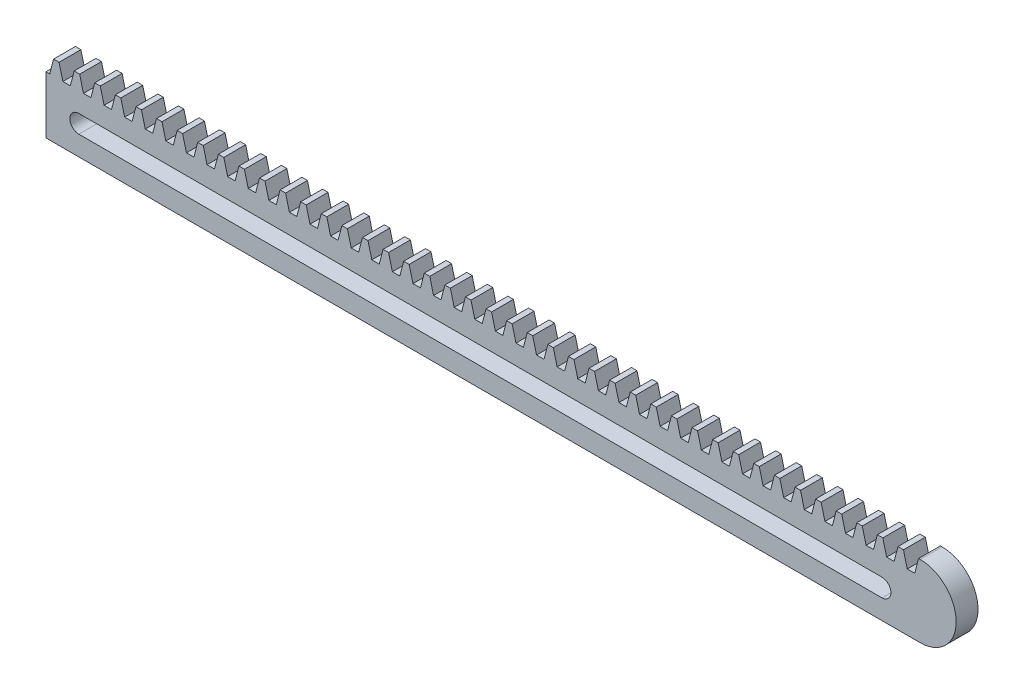
SolidWorks part; units mm, degrees
ref_plane "Plane1" through (0, 0, 0) normal (0, 0, 1) x (1, 0, 0)
ref_plane "Plane2" through (0, 0, 0) normal (0, 1, 0) x (1, 0, 0)
ref_plane "Plane3" through (0, 0, 0) normal (1, 0, 0) x (0, 0, -1)
sketch "HoldingSke" plane through (0, 0, 0) normal (0, 1, 0) x (1, 0, 0)
  line L0 (0, 0) -> (0.0464, 0.3301)
  line L1 (-15, 0) -> (100, 0) construction
  line L2 (0, 0) -> (-2.1039, 2.3779)
  line L3 (0, 0) -> (-11.863, 4.5341)
  line L4 (0, 0) -> (6.2122, 5.9991)
  line L5 (0, 0) -> (-23.7986, -8.8762)
  line L6 (0, 0) -> (-10.5278, -7.1032)
  line L9 (-67.7845, 28.3722) -> (319.4745, 128.5242)
  line L10 (-76.2, 5.3779) -> (-46.2, 5.3779)
  line L11 (0, 0) -> (-10, 0)
  line L12 (-76.2, 101.6) -> (-76.093, 101.6)
  line L13 (24.9733, 27.94) -> (52.9518, 28.4284)
  line L14 (24.9733, 27.94) -> (24.9743, 27.94)
  line L15 (24.9733, 27.94) -> (100.4006, 29.5858)
  circle A0 centre (0, 0) radius 19.05
  circle A1 centre (0, 0) radius 15
  circle A2 centre (0, 0) radius 12.7
  dimension "MPH" = 30
  dimension "Diameter" = 38.1
  dimension "Num_teeth" = 44
  dimension "Pitch" = 0.3333
  dimension "Width" = 10
  dimension "Show_teeth" = 998
  dimension "Thickness" = 12.7
  dimension "Ap" = 14.5
  dimension "Pitch_height" = 30
  dimension "Backlash" = 0.107
  dimension "Addendum_fac" = 1
  dimension "Dedendum_fac" = 1.25
  dimension "Clearance_fac" = 0.25
  dimension "Dedendum_add" = 0.001
  dimension "Length" = 400
  dimension "Module" = 3
sketch "BlankSke" plane through (0, 0, 0) normal (0, 0, 1) x (1, 0, 0)
  line L1 (0, 0) -> (400, 0)
  line L2 (0, 0) -> (0, 33)
  line L3 (0, 33) -> (400, 33)
  line L4 (400, 0) -> (400, 33)
  dimension "Length" = 400
  dimension "Blank_height" = 33
extrude "Blank" add sketch "BlankSke" against normal blind 10
sketch "TooCutSkeIll" plane through (0, 0, 0) normal (0, 0, 1) x (1, 0, 0)
  line L0 (-3.4298, 32.91) -> (-1.853, 26.813)
  line L1 (-1.1259, 26.25) -> (1.1259, 26.25)
  line L2 (1.853, 26.813) -> (3.4298, 32.91)
  line L3 (400, 33) -> (0, 33) construction
  line L4 (0, 0) -> (0, 64.897) construction
  line L5 (-13.208, 30) -> (12.954, 30) construction
  line L6 (0, 0) -> (400, 0) construction
  line L7 (2.6772, 30) -> (2.6772, 48.7463) construction
  line L8 (-2.6772, 30) -> (-2.6772, 48.7463) construction
  line L9 (3.546, 33) -> (3.546, 33.0254)
  line L10 (-3.546, 33) -> (-3.546, 33.0254)
  line L11 (-3.546, 33.0254) -> (3.546, 33.0254)
  arc A0 (1.1259, 26.25) -> (1.853, 26.813) centre (1.1259, 27.001) ccw
  arc A1 (-1.853, 26.813) -> (-1.1259, 26.25) centre (-1.1259, 27.001) ccw
  arc A2 (3.546, 33) -> (3.4298, 32.91) centre (3.546, 32.88) ccw
  arc A3 (-3.4298, 32.91) -> (-3.546, 33) centre (-3.546, 32.88) ccw
  dimension "Root_fillet" = 0.751
  dimension "Break_rad" = 0.12
  dimension "Pitch_height" = 30
  dimension "Gap_width" = 5.3544
  dimension "Dedendum" = 3.75
  dimension "Addendum_plus" = 3.0254
  dimension "Pressure_angle" = 14.5
extrude "ToothCutIll" [suppressed] cut sketch "TooCutSkeIll" against normal through all
sketch "TooCutSkeSim" plane through (0, 0, 0) normal (0, 0, 1) x (1, 0, 0)
  line L0 (1.7074, 26.25) -> (-1.7074, 26.25)
  line L1 (3.4596, 33.0254) -> (1.7074, 26.25)
  line L2 (0, 17.4625) -> (0, 53.467) construction
  line L3 (3.4596, 33.0254) -> (-3.4596, 33.0254)
  line L6 (-3.4596, 33.0254) -> (-1.7074, 26.25)
  line L9 (-2.6772, 30) -> (2.6772, 30) construction
  line L10 (0, 0) -> (400, 0) construction
  line L11 (2.6772, 30) -> (2.6772, 53.467) construction
  line L12 (-2.6772, 30) -> (-2.6772, 53.467) construction
  dimension "Pitch_height" = 30
  dimension "Pressure_angle" = 14.5
  dimension "Gap_width" = 5.3544
  dimension "Dedendum" = 3.75
  dimension "Addendum_plus" = 3.0254
extrude "ToothCutSim" cut sketch "TooCutSkeSim" against normal through all
pattern_linear "TeethCuts" count 43 spacing 9.4248 along (1, 0, 0) of "ToothCutIll", "ToothCutSim"
sketch "Sketch1" plane through (0, 0, 0) normal (0, 0, 1) x (1, 0, 0)
  line L0 (0, 26.25) -> (0, 0) construction
  line L1 (397.5481, 26.25) -> (397.5481, 0) construction
  line L2 (0, 0) -> (400, 0) construction
  line L3 (15, 13.125) -> (382.5481, 13.125) construction
  line L4 (15, 17.225) -> (382.5481, 17.225)
  line L5 (15, 9.025) -> (382.5481, 9.025)
  arc A0 (15, 17.225) -> (15, 9.025) centre (15, 13.125) ccw
  arc A1 (382.5481, 9.025) -> (382.5481, 17.225) centre (382.5481, 13.125) ccw
  point P11 (198.774, 13.125)
  point P16 (0, 13.125)
  dimension "D1" = 15
  dimension "D2" = 8.2
  dimension "D3" = 15
extrude "Cut-Extrude1" cut sketch "Sketch1" against normal through all
sketch "Sketch2" plane through (0, 0, -10) normal (0, 0, -1) x (-1, 0, 0)
  line L1 (-400, 0) -> (-400, 33) construction
  line L2 (-400, 33) -> (-400, 0)
  arc A0 (-400, 33) -> (-400, 0) centre (-400, 16.5) ccw
extrude "Boss-Extrude1" add sketch "Sketch2" against normal blind 10
equation "' \"Module@HoldingSke\" = 6.35"
equation "' \"Num_teeth@HoldingSke\" = 12"
equation "' \"Ap@HoldingSke\" =  20"
equation "' \"Width@HoldingSke\" = 0.25 * 25.4"
equation "' \"Show_teeth@HoldingSke\" = 500"
equation "' \"Backlash@HoldingSke\" = 0.009 * 25.4"
equation "' \"Addendum_fac@HoldingSke\" = 1.0"
equation "' \"Dedendum_fac@HoldingSke\" = 1.25"
equation "' \"Dedendum_add@HoldingSke\" = 0.00005 * 25.4"
equation "' \"Clearance_fac@HoldingSke\" = 0.25"
equation "' \"Pitch_height@HoldingSke\" = 1 * 25.4"
equation "' \"Length@HoldingSke\" = 4.71 * 25.4"
equation "\"Pitch@HoldingSke\" = 1 / \"Module@HoldingSke\""
equation "\"MPH@HoldingSke\" = \"Dedendum_fac@HoldingSke\" / \"Pitch@HoldingSke\" + 2 * \"Dedendum_add@HoldingSke\" + 0.002 * 25.4"
equation "\"MPH@HoldingSke\" = ((sgn( \"MPH@HoldingSke\" - \"Pitch_height@HoldingSke\")+1)*( \"MPH@HoldingSke\" - \"Pitch_height@HoldingSke\"))/2 + \"Pitch_height@HoldingSke\""
equation "\"Blank_height@BlankSke\" = \"Pitch_height@HoldingSke\" + \"Addendum_fac@HoldingSke\"  / \"Pitch@HoldingSke\" "
equation "\"Length@BlankSke\" =  \"Length@HoldingSke\""
equation "\"Face_width@Blank\" = \"Width@HoldingSke\""
equation "\"Pressure_angle@TooCutSkeIll\" = \"Ap@HoldingSke\""
equation "\"Addendum_plus@TooCutSkeIll\" =  \"Addendum_fac@HoldingSke\"  / \"Pitch@HoldingSke\" + 0.001 *25.4"
equation "\"Dedendum@TooCutSkeIll\" = \"Dedendum_fac@HoldingSke\"  / \"Pitch@HoldingSke\""
equation "\"Pitch_height@TooCutSkeIll\" =  \"MPH@HoldingSke\""
equation "\"Gap_width@TooCutSkeIll\" = 3.14159265 / 2 / \"Pitch@HoldingSke\" + 6 * \"Backlash@HoldingSke\""
equation "\"Pressure_angle@TooCutSkeSim\" = \"Ap@HoldingSke\""
equation "\"Addendum_plus@TooCutSkeSim\" =  \"Addendum_fac@HoldingSke\"  / \"Pitch@HoldingSke\" + 0.001 * 25.4"
equation "\"Dedendum@TooCutSkeSim\" = \"Dedendum_fac@HoldingSke\"  / \"Pitch@HoldingSke\""
equation "\"Pitch_height@TooCutSkeSim\" =  \"MPH@HoldingSke\""
equation "\"Gap_width@TooCutSkeSim\" = 3.14159265 / 2 / \"Pitch@HoldingSke\" + 6 * \"Backlash@HoldingSke\""
equation "\"Root_fillet@TooCutSkeIll\" = \"Clearance_fac@HoldingSke\" / \"Pitch@HoldingSke\" + \"Dedendum_add@HoldingSke\""
equation "\"Break_rad@TooCutSkeIll\" = 0.02 / \"Pitch@HoldingSke\" * 2"
equation "\"Linear_pitch@TeethCuts\" = 3.14159265 / \"Pitch@HoldingSke\""
equation "\"Num_teeth@HoldingSke\" = int( ( \"Length@HoldingSke\" + 0 ) / (3.14159265 / \"Pitch@HoldingSke\")) + 0.9999  + 1"
equation " \"Num_teeth@TeethCuts\" = int( \"Show_teeth@HoldingSke\" ) + 1"
equation " \"Num_teeth@TeethCuts\" = ((sgn( \"Num_teeth@TeethCuts\" - \"Num_teeth@HoldingSke\" )-1)*( \"Num_teeth@TeethCuts\" - \"Num_teeth@HoldingSke\" ))/-2+ \"Num_teeth@HoldingSke\""
equation " \"Num_teeth@TeethCuts\" = ((sgn( \"Num_teeth@TeethCuts\" - 2.0)+1)*( \"Num_teeth@TeethCuts\" - 2.0))/2 +2.0"
